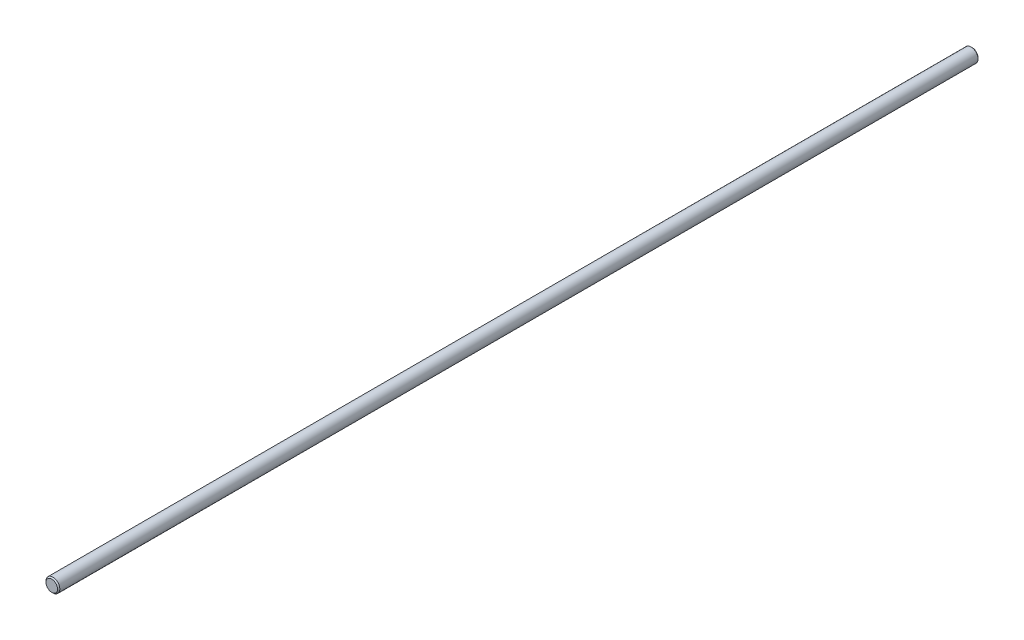
SolidWorks part; units mm, degrees
material "普通碳钢"
ref_plane "前视基准面" through (0, 0, 0) normal (0, 0, 1) x (1, 0, 0)
ref_plane "上视基准面" through (0, 0, 0) normal (0, 1, 0) x (1, 0, 0)
ref_plane "右视基准面" through (0, 0, 0) normal (1, 0, 0) x (0, 0, -1)
other "Configuration Table"
sketch "草图1" plane through (0, 0, 0) normal (0, 0, 1) x (1, 0, 0)
  circle A0 centre (0, 0) radius 3
  dimension "D1" = 6
extrude "凸台-拉伸1" add sketch "草图1" along normal mid plane 400
chamfer "倒角1" distance 0.5 angle 45 2 edges at (3, 0, 200) (3, 0, -200)
